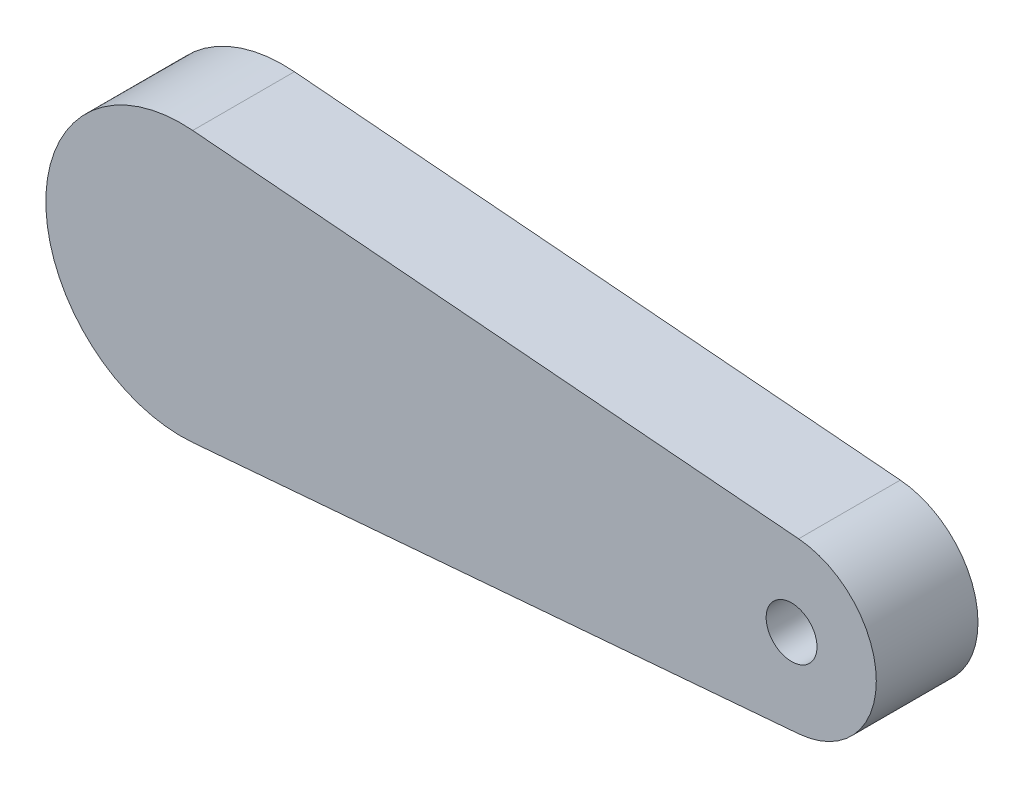
SolidWorks part; units mm, degrees
ref_plane "Front Plane" through (0, 0, 0) normal (0, 0, 1) x (1, 0, 0)
ref_plane "Top Plane" through (0, 0, 0) normal (0, 1, 0) x (1, 0, 0)
ref_plane "Right Plane" through (0, 0, 0) normal (1, 0, 0) x (0, 0, -1)
sketch "Sketch1" plane through (0, 0, 0) normal (0, 0, 1) x (1, 0, 0)
  line L0 (3.3333, 39.8609) -> (182.0833, 24.913)
  line L1 (3.3333, -39.8609) -> (182.0833, -24.913)
  arc A0 (3.3333, 39.8609) -> (3.3333, -39.8609) centre (0, 0) ccw
  arc A1 (182.0833, -24.913) -> (182.0833, 24.913) centre (180, 0) ccw
  dimension "D1" = 80
  dimension "D2" = 50
  dimension "D3" = 180
extrude "Boss-Extrude1" add sketch "Sketch1" along normal blind 30
sketch "Sketch2" plane through (0, 0, 0) normal (0, 0, -1) x (-1, 0, 0)
  circle A0 centre (0, 0) radius 5
  dimension "D1" = 10
extrude "Cut-Extrude1" cut sketch "Sketch2" against normal blind 10
sketch "Sketch3" plane through (0, 0, 30) normal (0, 0, 1) x (1, 0, 0)
  circle A0 centre (180, 0) radius 7.5
  dimension "D1" = 15
extrude "Cut-Extrude2" cut sketch "Sketch3" against normal blind 69
sketch "Sketch4" plane through (0, 0, 0) normal (0, 0, -1) x (-1, 0, 0)
  line L0 (0, 0) -> (-100, 0) construction
  line L1 (-100, 0) -> (0, 0) construction
  line L2 (0, 0) -> (0, 100) construction
  text T0 "X1\r\n" font "Century Gothic" height 20
  text T1 "Y1\r\n" font "Century Gothic" height 20
  dimension "D1" = 100
sketch "Sketch5" plane through (0, 0, 0) normal (0, 1, 0) x (1, 0, 0)
  line L0 (0, 0) -> (0, -100) construction
  line L1 (0, 0) -> (100, 0) construction
  text T0 "Z1" font "Century Gothic" height 20
sketch "Sketch6" plane through (0, 0, 0) normal (0, 0, -1) x (-1, 0, 0)
  line L0 (-180, 0) -> (-280, 0) construction
  line L1 (-280, 0) -> (-180, 0) construction
  line L2 (-180, 0) -> (-180, -100) construction
  circle A0 centre (-180, 0) radius 7.5 construction
  text T0 "X2" font "Century Gothic" height 20
  text T1 "Y2" font "Century Gothic" height 20
  dimension "D1" = 100
sketch "Sketch7" plane through (0, 0, 0) normal (0, 1, 0) x (1, 0, 0)
  line L0 (180, 0) -> (180, 100) construction
  line L1 (180, 0) -> (280, 0) construction
  text T0 "Z2" font "Century Gothic" height 20
